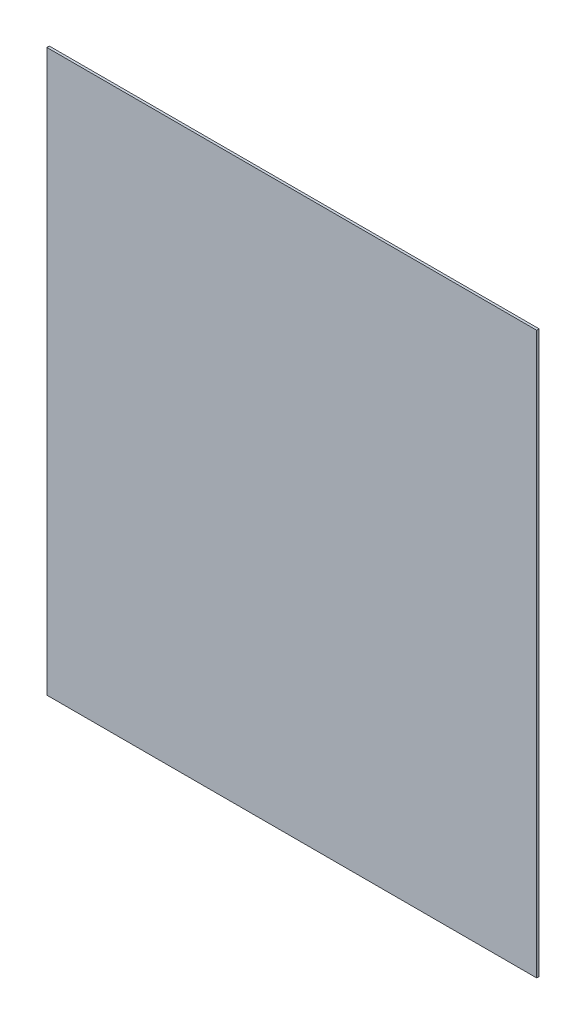
SolidWorks part; units mm, degrees
ref_plane "Front" through (0, 0, 0) normal (0, 0, 1) x (1, 0, 0)
ref_plane "Top" through (0, 0, 0) normal (0, 1, 0) x (1, 0, 0)
ref_plane "Right" through (0, 0, 0) normal (1, 0, 0) x (0, 0, -1)
sketch "Sketch2" plane through (0, 0, 0) normal (0, 0, 1) x (1, 0, 0)
  line L1 (-254, -290.83) -> (254, -290.83)
  line L2 (-254, -290.83) -> (-254, 290.83)
  line L3 (-254, 290.83) -> (254, 290.83)
  line L4 (254, -290.83) -> (254, 290.83)
  line L5 (-254, -290.83) -> (254, 290.83) construction
  line L6 (-254, 290.83) -> (254, -290.83) construction
  point P0 (0, 0)
  dimension "D1" = 508
  dimension "D2" = 581.66
extrude "Boss-Extrude1" add sketch "Sketch2" along normal blind 2.54
